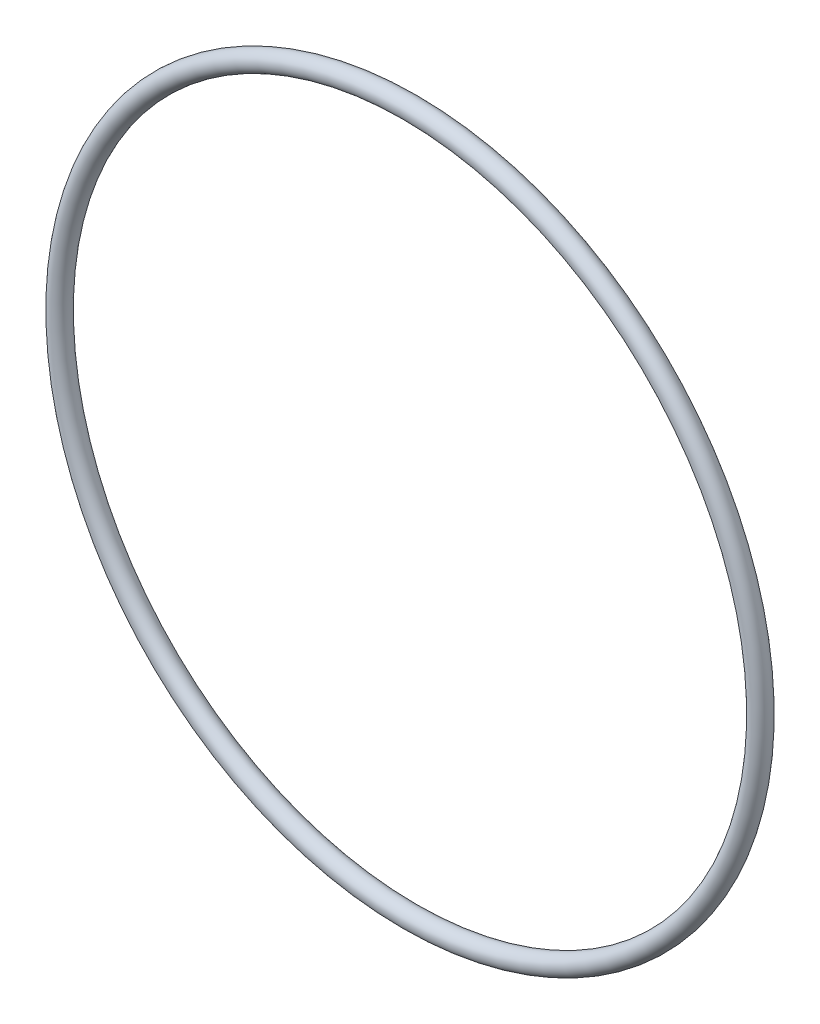
SolidWorks part; units mm, degrees
ref_plane "Front Plane" through (0, 0, 0) normal (0, 0, 1) x (1, 0, 0)
ref_plane "Top Plane" through (0, 0, 0) normal (0, 1, 0) x (1, 0, 0)
ref_plane "Right Plane" through (0, 0, 0) normal (1, 0, 0) x (0, 0, -1)
sketch "Sketch1" plane through (0, 0, 0) normal (1, 0, 0) x (0, 0, -1)
  line L0 (0, -61.7093) -> (0, 61.7093) construction
  circle A0 centre (0, -63.4746) radius 1.7653 construction
  circle A1 centre (0, 63.4746) radius 1.7653 construction
  point P3 (-1.7653, -61.7093)
  point P4 (0, 0)
  point P7 (0, -65.2399)
  point P8 (-1.7653, -63.4746)
  point P9 (1.7653, -63.4746)
  point P12 (0, 65.2399)
  dimension "ID" = 123.4186
  dimension "OD" = 130.4798
  dimension "Width" = 3.5306
sketch "Sketch2" plane through (0, 0, 0) normal (1, 0, 0) x (0, 0, -1)
  line L0 (-61.7093, 0) -> (61.7093, 0) construction
  line L1 (0, -61.7093) -> (0, 61.7093) construction
  circle A0 centre (0, 63.4746) radius 1.7653 construction
  circle A1 centre (0, 63.4746) radius 1.7653
  point P7 (0, 0)
revolve "Revolve1" add sketch "Sketch2" angle 360 about L0
sketch "Drawing Reference 1" plane through (0, 0, 0) normal (0, 0, 1) x (1, 0, 0)
  circle A0 centre (0, 0) radius 65.2399
  circle A1 centre (0, 0) radius 61.7093
